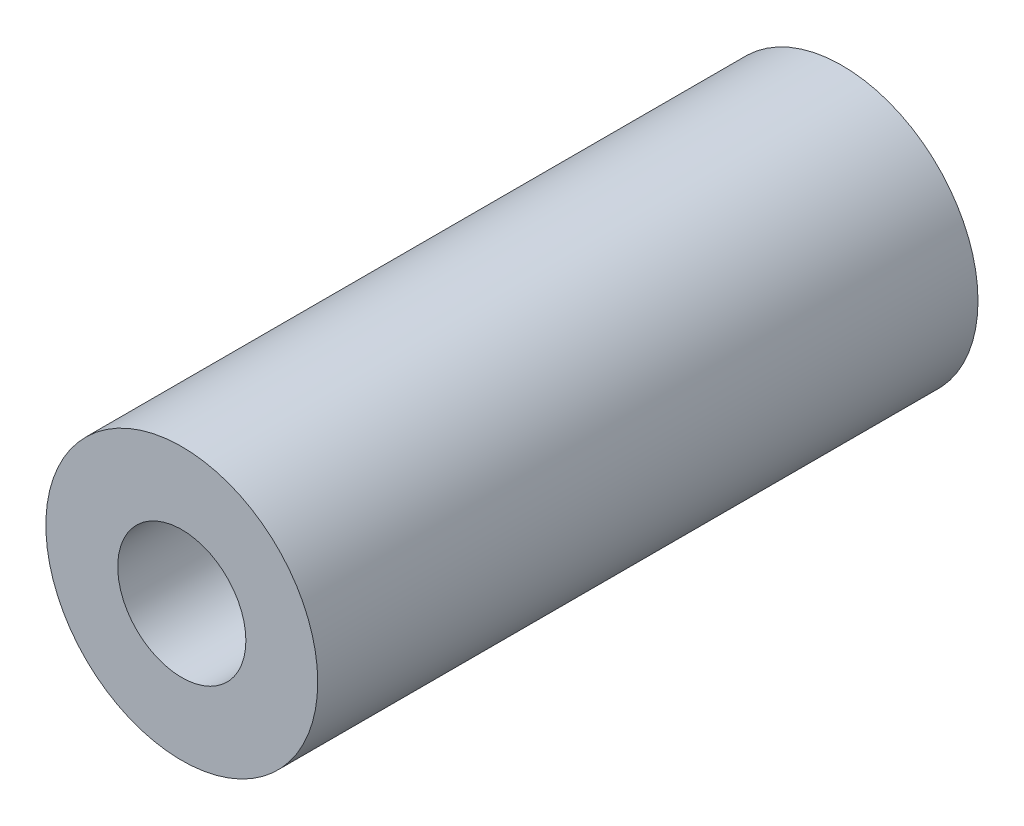
SolidWorks part; units mm, degrees
ref_plane "Front Plane" through (0, 0, 0) normal (0, 0, 1) x (1, 0, 0)
ref_plane "Top Plane" through (0, 0, 0) normal (0, 1, 0) x (1, 0, 0)
ref_plane "Right Plane" through (0, 0, 0) normal (1, 0, 0) x (0, 0, -1)
sketch "S01 - Annular section" plane through (0, 0, 0) normal (0, 0, 1) x (1, 0, 0)
  circle A0 centre (0, 0) radius 7
  circle A1 centre (0, 0) radius 3.3
  dimension "D1" = 6.6
  dimension "D2" = 14
extrude "01 - Annular section" add sketch "S01 - Annular section" along normal blind 34
